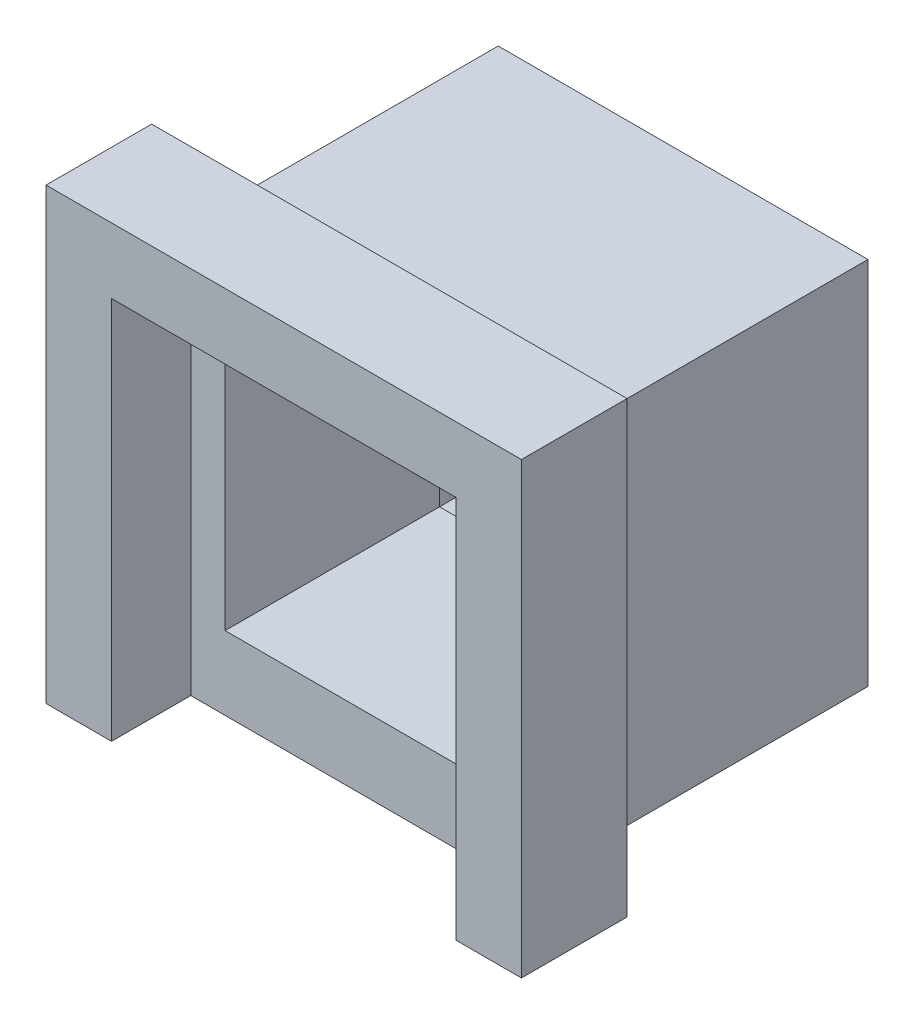
SolidWorks part; units mm, degrees
material "ABS PC"
ref_plane "Front Plane" through (0, 0, 0) normal (0, 0, 1) x (1, 0, 0)
ref_plane "Top Plane" through (0, 0, 0) normal (0, 1, 0) x (1, 0, 0)
ref_plane "Right Plane" through (0, 0, 0) normal (1, 0, 0) x (0, 0, -1)
sketch "Sketch2" plane through (0, 0, 0) normal (0, 0, 1) x (1, 0, 0)
  line L1 (1.305, -1.305) -> (-1.305, -1.305)
  line L2 (1.305, -1.305) -> (1.305, 1.305)
  line L3 (1.305, 1.305) -> (-1.305, 1.305)
  line L4 (-1.305, -1.305) -> (-1.305, 1.305)
  line L5 (1.305, -1.305) -> (-1.305, 1.305) construction
  line L6 (1.305, 1.305) -> (-1.305, -1.305) construction
  line L7 (1.75, -1.75) -> (-1.75, -1.75)
  line L8 (1.75, -1.75) -> (1.75, 1.75)
  line L9 (1.75, 1.75) -> (-1.75, 1.75)
  line L10 (-1.75, -1.75) -> (-1.75, 1.75)
  line L11 (1.75, -1.75) -> (-1.75, 1.75) construction
  line L12 (1.75, 1.75) -> (-1.75, -1.75) construction
  point P0 (0, 0)
  point P5 (0, 0)
  dimension "D1" = 2.61
  dimension "D2" = 3.5
extrude "Boss-Extrude1" add sketch "Sketch2" along normal blind 3.78
sketch "Sketch3" plane through (0, 0, 0) normal (0, 0, 1) x (1, 0, 0)
  line L1 (-1.55, -1.55) -> (1.55, -1.55)
  line L2 (-1.55, -1.55) -> (-1.55, 1.55)
  line L3 (-1.55, 1.55) -> (1.55, 1.55)
  line L4 (1.55, -1.55) -> (1.55, 1.55)
  line L5 (-1.55, -1.55) -> (1.55, 1.55) construction
  line L6 (-1.55, 1.55) -> (1.55, -1.55) construction
  line L8 (-1.305, -1.305) -> (1.305, -1.305)
  line L9 (-1.305, -1.305) -> (-1.305, 1.305)
  line L10 (-1.305, 1.305) -> (1.305, 1.305)
  line L11 (1.305, -1.305) -> (1.305, 1.305)
  line L12 (-1.305, -1.305) -> (1.305, 1.305) construction
  line L13 (-1.305, 1.305) -> (1.305, -1.305) construction
  point P0 (0, 0)
  point P8 (0, 0)
  dimension "D1" = 3.1
extrude "Cut-Extrude1" cut sketch "Sketch3" along normal blind 1
sketch "Sketch4" plane through (0, 0, 3.78) normal (0, 0, 1) x (1, 0, 0)
  line L1 (-1.75, -1.75) -> (1.75, -1.75) construction
  line L3 (-2.25, 2.25) -> (2.25, 2.25)
  line L4 (1.75, -1.75) -> (1.75, 1.75) construction
  line L5 (-1.75, -1.75) -> (1.75, -1.75)
  line L6 (-1.75, 1.75) -> (-1.75, -1.75) construction
  line L7 (1.75, 1.75) -> (-1.75, 1.75) construction
  line L8 (1.75, -1.75) -> (1.75, 1.75)
  line L9 (-2.25, 2.25) -> (-2.25, -2)
  line L10 (-2.25, -2) -> (2.25, -2)
  line L11 (2.25, -2) -> (2.25, 2.25)
  line L12 (-1.75, 1.75) -> (-1.75, -1.75)
  line L13 (1.75, 1.75) -> (-1.75, 1.75)
  point P6 (-1.75, 0)
  dimension "D1" = 0.5
  dimension "D2" = 0.5
  dimension "D3" = 0.25
  dimension "D4" = 0.5
extrude "Boss-Extrude2" add sketch "Sketch4" against normal blind 1
sketch "Sketch5" plane through (0, 0, 3.78) normal (0, 0, 1) x (1, 0, 0)
  line L0 (-1.305, 1.305) -> (-1.305, -1.305) construction
  line L1 (-1.585, 1.585) -> (1.585, 1.585) construction
  line L2 (-1.585, 1.585) -> (-1.585, -3.025) construction
  line L3 (-1.585, -3.025) -> (1.585, -3.025) construction
  line L4 (1.585, 1.585) -> (1.585, -3.025) construction
  line L5 (1.305, 1.305) -> (-1.305, 1.305) construction
  line L6 (1.305, -1.305) -> (1.305, 1.305) construction
  line L7 (-1.63, 1.63) -> (1.63, 1.63)
  line L8 (-1.63, 1.63) -> (-1.63, -4.3736)
  line L9 (-1.63, -4.3736) -> (1.63, -4.3736)
  line L10 (1.63, 1.63) -> (1.63, -4.3736)
  dimension "D1" = 3.17
  dimension "D2" = 4.61
  dimension "D3" = 0.28
  dimension "D4" = 0.28
  dimension "D5" = 0.325
  dimension "D6" = 0.325
  dimension "D7" = 0.325
extrude "Cut-Extrude2" cut sketch "Sketch5" against normal blind 0.75
